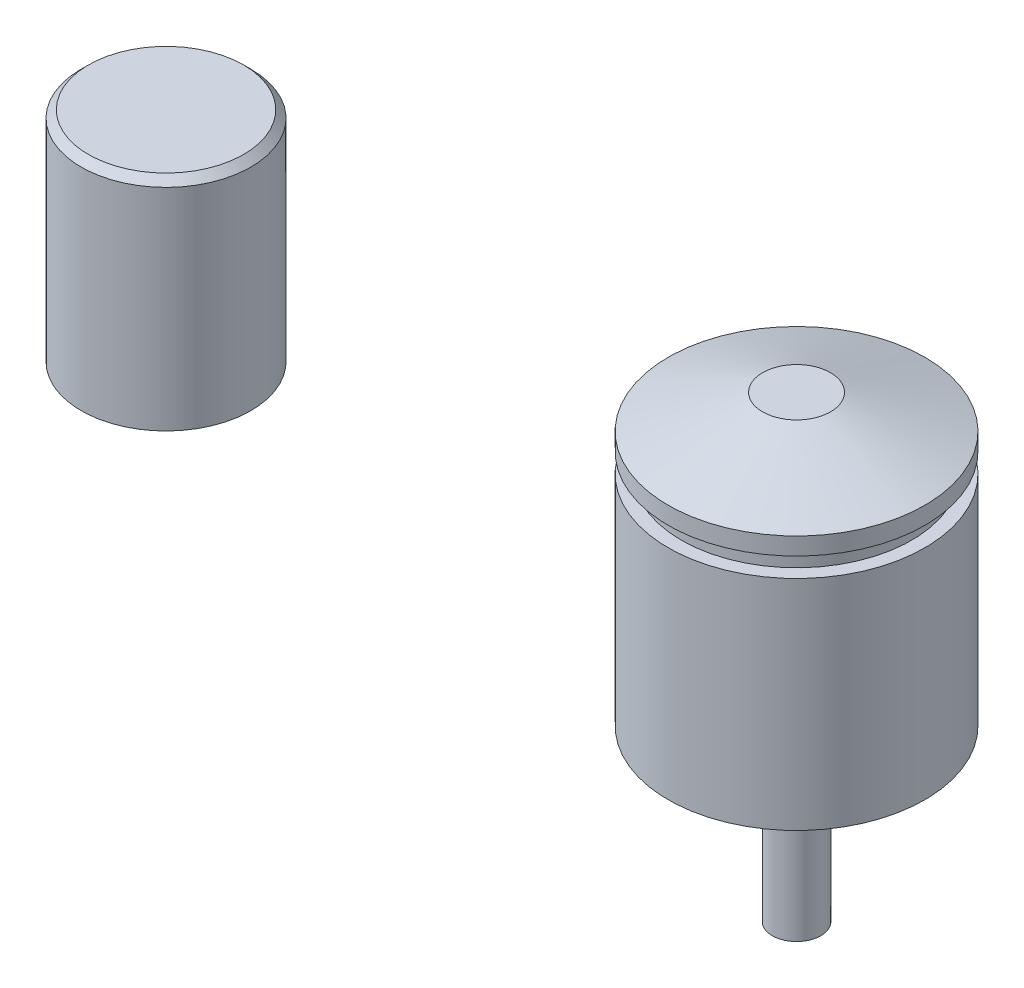
SolidWorks part; units mm, degrees
ref_plane "Спереди" through (0, 0, 0) normal (0, 0, 1) x (1, 0, 0)
ref_plane "Сверху" through (0, 0, 0) normal (0, 1, 0) x (1, 0, 0)
ref_plane "Справа" through (0, 0, 0) normal (1, 0, 0) x (0, 0, -1)
sketch "Эскиз1" plane through (0, 0, 0) normal (0, 0, 1) x (1, 0, 0)
  line L0 (0, 38.6) -> (0, 42.8365) construction
  line L1 (1.75, 38.6) -> (-1.75, 38.6) construction
  line L2 (0, 37.3339) -> (-0.7817, 37.3339)
  line L3 (-0.7817, 37.3339) -> (-0.7817, 34.1)
  line L4 (-1.75, 34.1) -> (1.75, 34.1) construction
  line L5 (-0.7817, 34.1) -> (-1.75, 34.1)
  line L6 (-1.75, 34.1) -> (-1.75, 38.6)
  line L7 (20.5, 38.6) -> (-20.5, 38.6) construction
  line L8 (-1.75, 38.6) -> (0, 38.6)
  line L9 (0, 38.6) -> (0, 37.3339)
  point P7 (-0.3908, 37.3339)
  dimension "D1" = 1.2661
  dimension "D2" = 3.2339
revolve "Повернуть1" add sketch "Эскиз1" angle 360 about L0
sketch "Эскиз3" plane through (0, 0, 0) normal (0, 0, 1) x (1, 0, 0)
  line L0 (13, 34.1) -> (13, 42.0852) construction
  line L1 (10.3544, 34.1) -> (15.6456, 34.1) construction
  line L2 (12.5, 34.1) -> (10.3544, 34.1)
  line L3 (10.3544, 34.1) -> (10.3544, 38.6)
  line L4 (15.6456, 38.6) -> (10.3544, 38.6) construction
  line L5 (10.3544, 38.6) -> (10.625, 38.6)
  line L6 (10.625, 38.6) -> (15.375, 38.6) construction
  line L7 (10.625, 38.6) -> (10.625, 39)
  line L8 (15.375, 39) -> (10.625, 39) construction
  line L9 (10.625, 39) -> (10.3544, 39)
  line L10 (15.8869, 39) -> (10.1131, 39) construction
  line L11 (10.3544, 39) -> (10.3544, 39.3587)
  line L12 (10.3544, 39.3587) -> (12.3, 40.0551)
  line L13 (12.3, 40.0551) -> (13, 40.0551)
  line L14 (13, 40.0551) -> (13, 34.1)
  line L15 (13, 34.1) -> (13, 30.6)
  line L16 (13, 30.6) -> (12.5, 30.6)
  line L17 (12.5, 30.6) -> (12.5, 34.1)
  dimension "D1" = 2.6456
  dimension "D2" = 5.9551
  dimension "D3" = 0.7
  dimension "D4" = 2.375
  dimension "D5" = 3.5
  dimension "D6" = 0.5
revolve "Повернуть2" add sketch "Эскиз3" angle 360 about L0
chamfer "Фаска1" distance 0.15 angle 45 1 edges at (0, 38.6, -1.75)
